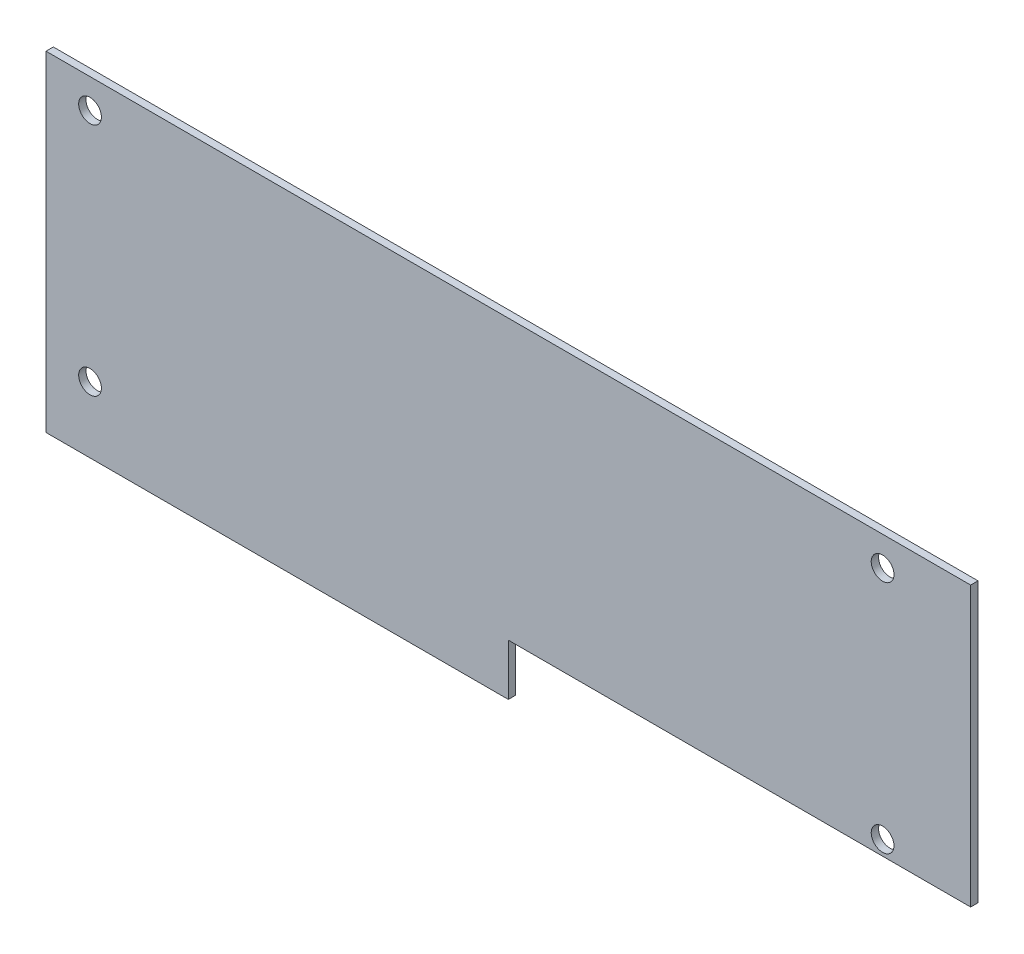
SolidWorks part; units mm, degrees
ref_plane "Płaszczyzna przednia" through (0, 0, 0) normal (0, 0, 1) x (1, 0, 0)
ref_plane "Płaszczyzna górna" through (0, 0, 0) normal (0, 1, 0) x (1, 0, 0)
ref_plane "Płaszczyzna prawa" through (0, 0, 0) normal (1, 0, 0) x (0, 0, -1)
sketch "Szkic1" plane through (0, 0, 0) normal (0, 0, 1) x (1, 0, 0)
  line L0 (-118.0507, 36.1882) -> (-55.0507, 36.1882)
  line L2 (-55.0507, 36.1882) -> (-55.0507, 43.1882)
  line L4 (-118.0507, 36.1882) -> (-118.0507, 81.1882)
  line L6 (-55.0507, 43.1882) -> (7.9493, 43.1882)
  line L7 (7.9493, 81.1882) -> (7.9493, 43.1882)
  line L16 (-118.0507, 81.1882) -> (7.9493, 81.1882)
  point P0 (-167.4006, 82.1882)
  point P7 (-118.9006, 82.1882)
  point P11 (-167.9006, 73.6882)
  point P12 (-118.9006, 74.1882)
  point P13 (-167.4006, 74.1882)
  point P14 (-118.4006, 73.6882)
  point P15 (-118.4006, 82.6882)
  point P16 (-167.9006, 82.6882)
  dimension "D3" = 63
  dimension "D5" = 38
  dimension "D7" = 7
  dimension "D8" = 45
extrude "Dodanie-wyciągnięcie1" add sketch "Szkic1" along normal blind 1
sketch "Szkic2" plane through (0, 0, 1) normal (0, 0, 1) x (1, 0, 0)
  circle A4 centre (-112.0507, 77.1882) radius 1.55
  circle A5 centre (-112.0507, 45.1882) radius 1.55
  circle A6 centre (-4.0507, 77.1882) radius 1.55
  circle A7 centre (-4.0507, 45.1882) radius 1.55
extrude "Wytnij-wyciągnięcie1" cut sketch "Szkic2" against normal blind 10
sketch "Szkic3" plane through (0, 0, 1) normal (0, 0, 1) x (1, 0, 0)
  circle A2 centre (-19.0507, 78.1882) radius 2.5
  circle A3 centre (-12.0507, 78.1882) radius 2.5
